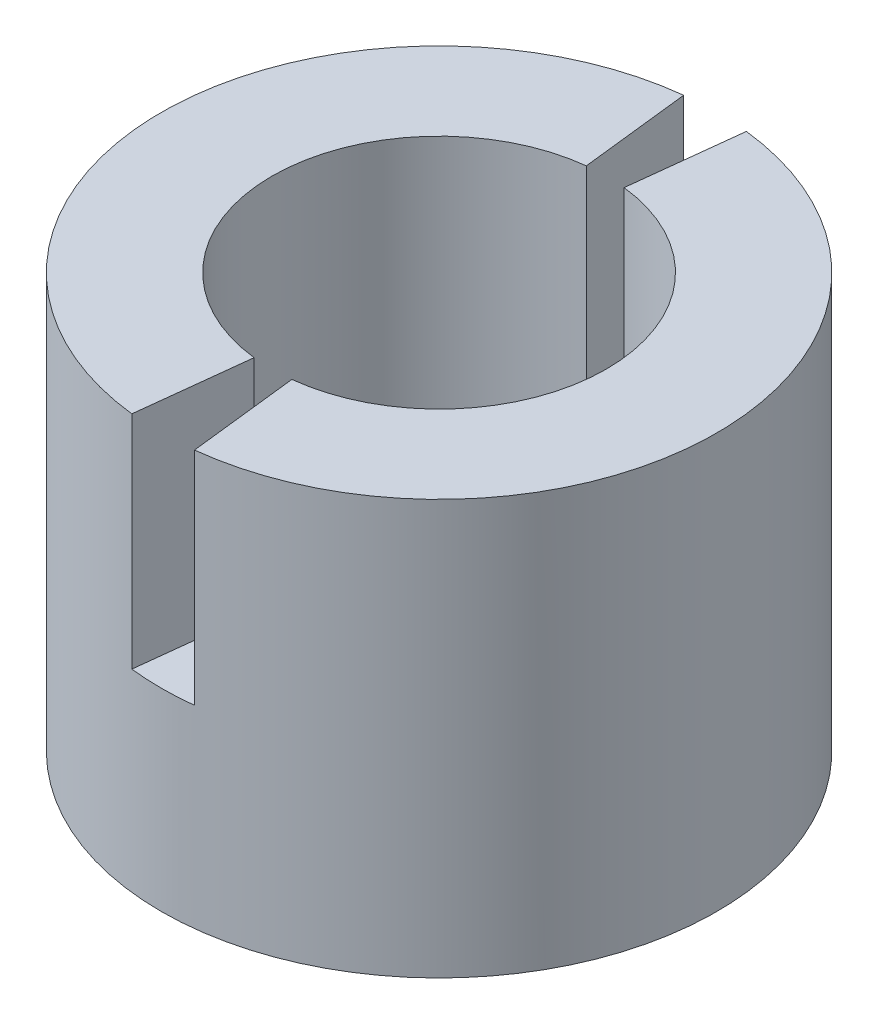
SolidWorks part; units mm, degrees
ref_plane "Front Plane" through (0, 0, 0) normal (0, 0, 1) x (1, 0, 0)
ref_plane "Top Plane" through (0, 0, 0) normal (0, 1, 0) x (1, 0, 0)
ref_plane "Right Plane" through (0, 0, 0) normal (1, 0, 0) x (0, 0, -1)
sketch "Sketch1" plane through (0, 0, 0) normal (0, 1, 0) x (1, 0, 0)
  circle A0 centre (0, 0) radius 6.05
  circle A1 centre (0, 0) radius 10.05
  dimension "D1" = 12.1
  dimension "D2" = 4
extrude "Boss-Extrude1" add sketch "Sketch1" along normal blind 15
sketch "Sketch3" plane through (0, 0, 0) normal (0, 0, 1) x (1, 0, 0)
  line L0 (-10.05, 0) -> (10.05, 12)
  line L1 (10.05, 0) -> (10.05, 15) construction
  line L2 (10.05, 12) -> (10.05, 0)
  line L3 (10.05, 0) -> (-10.05, 0)
  dimension "D1" = 12
sketch "Sketch6" plane through (0, 15, 0) normal (0, 1, 0) x (1, 0, 0)
  line L0 (-0.6373, 5.6108) -> (0.6373, 5.6108)
  line L1 (0.6373, 5.6108) -> (1.2157, 10.7035)
  line L2 (1.2157, 10.7035) -> (-1.2157, 10.7035)
  line L3 (0, -12.985) -> (0, 12.985) construction
  line L4 (-0.6373, 5.6108) -> (-1.2157, 10.7035)
  line L5 (-11.7237, 0) -> (13.1699, 0) construction
  line L6 (-0.6373, -5.6108) -> (-1.2157, -10.7035)
  line L7 (1.2157, -10.7035) -> (-1.2157, -10.7035)
  line L8 (0.6373, -5.6108) -> (1.2157, -10.7035)
  line L9 (-0.6373, -5.6108) -> (0.6373, -5.6108)
  point P8 (0, 10.7035)
  point P9 (0, 5.6108)
  point P12 (0, 0)
  point P16 (0, -5.6108)
  point P17 (0, -10.7035)
extrude "Cut-Extrude2" cut sketch "Sketch6" against normal blind 8
